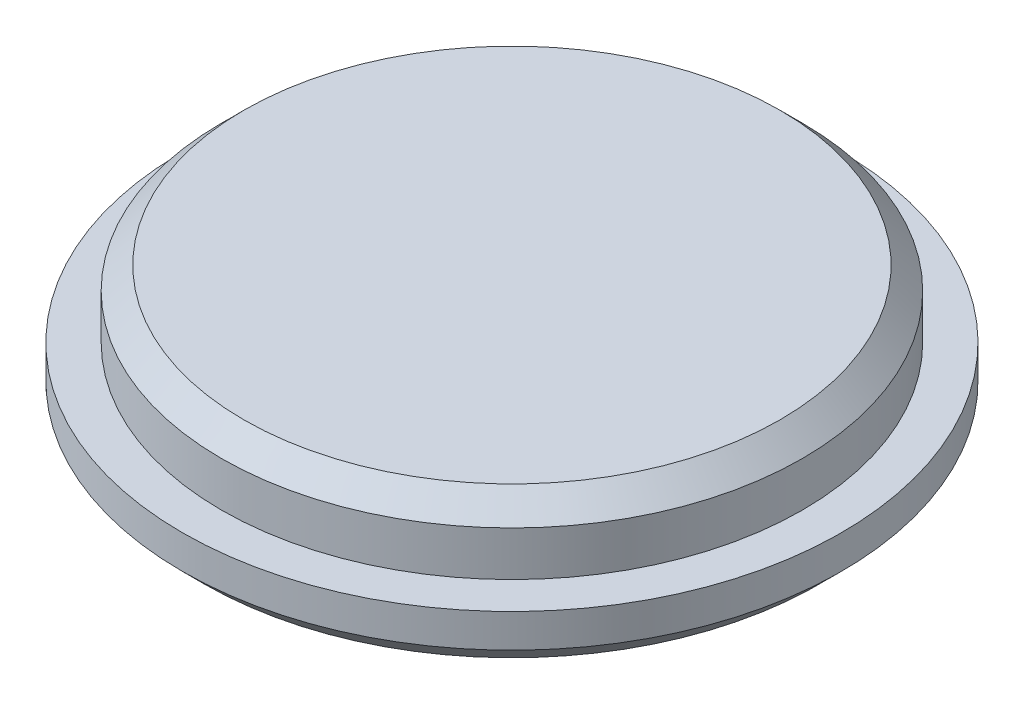
SolidWorks part; units mm, degrees
ref_plane "Front Plane" through (0, 0, 0) normal (0, 0, 1) x (1, 0, 0)
ref_plane "Top Plane" through (0, 0, 0) normal (0, 1, 0) x (1, 0, 0)
ref_plane "Right Plane" through (0, 0, 0) normal (1, 0, 0) x (0, 0, -1)
sketch "Sketch2" plane through (0, 0, 0) normal (0, 0, 1) x (1, 0, 0)
  line L0 (0, 0) -> (27.5, 0)
  line L1 (0, 0) -> (0, -50000) construction
  line L2 (29.5, 2) -> (29.5, 5)
  line L3 (26, 5) -> (26, 9)
  line L4 (26, 5) -> (29.5, 5)
  line L5 (24, 11) -> (0, 11)
  line L6 (0, 11) -> (0, 0)
  line L7 (27.5, 0) -> (29.5, 2)
  line L8 (26, 9) -> (24, 11)
  point P1 (29.5, 0)
  point P8 (26, 11)
revolve "Revolve1" add sketch "Sketch2" angle 360 about L1
